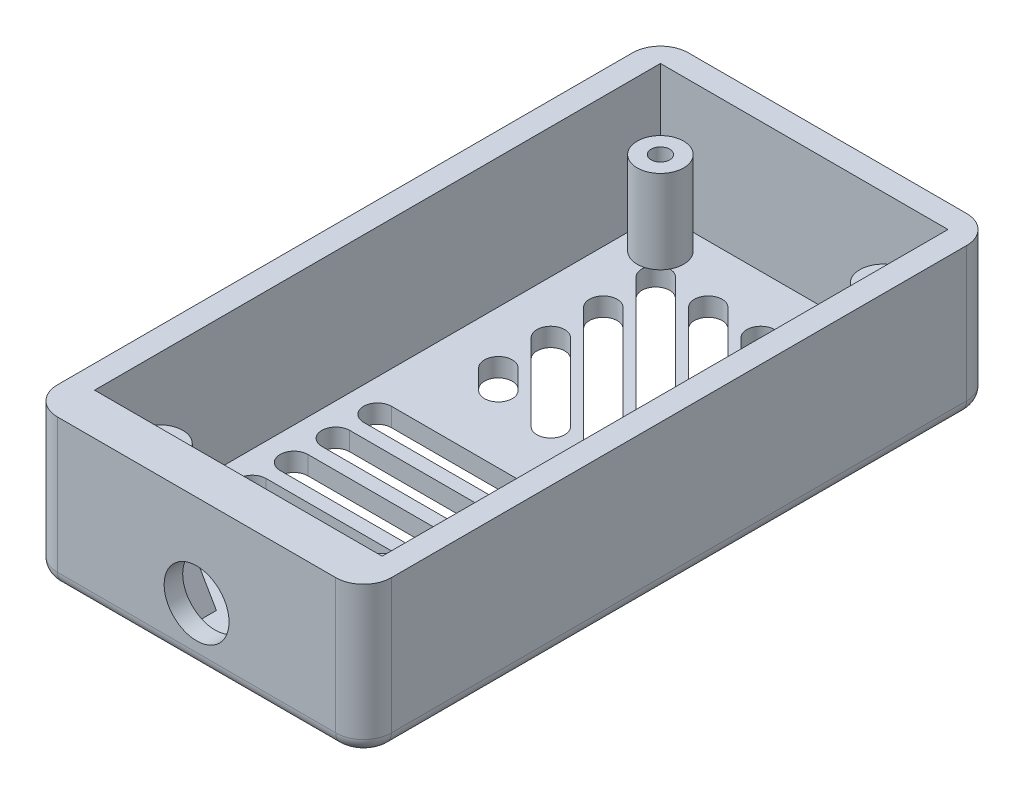
SolidWorks part; units mm, degrees
ref_plane "前视基准面" through (0, 0, 0) normal (0, 0, 1) x (1, 0, 0)
ref_plane "上视基准面" through (0, 0, 0) normal (0, 1, 0) x (1, 0, 0)
ref_plane "右视基准面" through (0, 0, 0) normal (1, 0, 0) x (0, 0, -1)
sketch "草图1" plane through (0, 0, 0) normal (0, 1, 0) x (1, 0, 0)
  line L0 (-15, 30) -> (15, -30) construction
  line L1 (18, -33) -> (-18, -33)
  line L2 (18, -33) -> (18, 33)
  line L3 (18, 33) -> (-18, 33)
  line L4 (-18, -33) -> (-18, 33)
  line L5 (18, -33) -> (-18, 33) construction
  line L6 (18, 33) -> (-18, -33) construction
  line L11 (15.9587, -29.2575) -> (-14.6614, 26.8792) construction
  line L12 (15, 28.2353) -> (-15, -28.2353) construction
  line L13 (-15, 30) -> (15, 30)
  line L14 (-15, 30) -> (-15, -30)
  line L15 (-15, -30) -> (15, -30)
  line L16 (15, 30) -> (15, -30)
  line L17 (0, -30) -> (0, 30) construction
  line L18 (15, 0) -> (-15, 0) construction
  circle A0 centre (-12, 27) radius 1.05
  circle A1 centre (12, 27) radius 1.05
  circle A2 centre (12, -27) radius 1.05
  circle A3 centre (-12, -27) radius 1.05
  point P0 (0, 0)
  point P6 (0, 0)
  point P15 (0, 0)
  dimension "D6" = 3
  dimension "D7" = 2.1
  dimension "D1" = 36
  dimension "D2" = 66
  dimension "D3" = 60
  dimension "D4" = 30
  dimension "D5" = 3
extrude "凸台-拉伸1" add sketch "草图1" along normal blind 16 contours L4 L1 L2 L3 L13 L16 L15 L14 | L16 L13 L14 L15 A1 A0 A2 A3 | A3 | A2 | A0 | A1
sketch "草图2" plane through (0, 16, 0) normal (0, 1, 0) x (1, 0, 0)
  line L0 (15.5, -30.5) -> (-15.5, 30.5) construction
  line L1 (-15.5, 30.5) -> (15.5, 30.5)
  line L2 (-15.5, 30.5) -> (-15.5, -30.5)
  line L3 (-15.5, -30.5) -> (15.5, -30.5)
  line L4 (15.5, 30.5) -> (15.5, -30.5)
  point P6 (0, 0)
  dimension "D1" = 31
  dimension "D2" = 61
extrude "切除-拉伸1" cut sketch "草图2" against normal blind 14
sketch "草图3" plane through (0, 2, 0) normal (0, 1, 0) x (1, 0, 0)
  circle A0 centre (-12, 27) radius 2.5
  circle A1 centre (12, 27) radius 2.5
  circle A2 centre (12, -27) radius 2.5
  circle A3 centre (-12, -27) radius 2.5
  circle A4 centre (-12, 27) radius 1
  circle A5 centre (12, 27) radius 1
  circle A6 centre (12, -27) radius 1
  circle A7 centre (-12, -27) radius 1
  dimension "D1" = 5
extrude "凸台-拉伸4" add sketch "草图3" along normal blind 9 separate body
sketch "草图6" plane through (0, 0, 33) normal (0, 0, 1) x (1, 0, 0)
  line L1 (-18, 0) -> (18, 0)
  line L2 (-18, 0) -> (-18, 16)
  line L3 (-18, 16) -> (18, 16)
  line L4 (18, 0) -> (18, 16)
extrude "凸台-拉伸5" add sketch "草图6" along normal blind 2
sketch "草图7" plane through (0, 0, 30.5) normal (0, 0, -1) x (-1, 0, 0)
  line L0 (-18, 0) -> (18, 0) construction
  line L1 (2.3671, 10.2) -> (-2.3671, 10.2)
  line L2 (-2.3671, 10.2) -> (-4.7343, 6.1)
  line L3 (-4.7343, 6.1) -> (-2.3671, 2)
  line L4 (-2.3671, 2) -> (2.3671, 2)
  line L5 (2.3671, 2) -> (4.7343, 6.1)
  line L6 (4.7343, 6.1) -> (2.3671, 10.2)
  line L7 (0, 6.1) -> (0, 0) construction
  circle A0 centre (0, 6.1) radius 4.1 construction
  dimension "D1" = 2
  dimension "D2" = 8.2
extrude "切除-拉伸2" cut sketch "草图7" against normal blind 2.5
sketch "草图9" plane through (0, 0, 33) normal (0, 0, -1) x (-1, 0, 0)
  line L0 (4.7343, 6.1) -> (-4.7343, 6.1) construction
  line L1 (2.3671, 2) -> (4.7343, 6.1) construction
  line L2 (-4.7343, 6.1) -> (-2.3671, 2) construction
  circle A0 centre (0, 6.1) radius 3.5
  dimension "D1" = 7
extrude "切除-拉伸3" cut sketch "草图9" against normal through all
fillet "圆角1" radius 3 4 edges at (-18, 8, 35) (18, 8, 35) (18, 8, -33) (-18, 8, -33)
fillet "圆角2" radius 1.5 8 edges at (17.1213, 0, 34.1213) (18, 0, 1) (17.1213, 0, -32.1213) (0, 0, -33) (-17.1213, 0, -32.1213) (-18, 0, 1) (-17.1213, 0, 34.1213) (0, 0, 35)
sketch "草图13" plane through (0, 0, 0) normal (0, -1, 0) x (1, 0, 0)
  line L24 (-12, 17) -> (12, 17) construction
  line L25 (0, 0) -> (0, -14.5) construction
  line L26 (-12, 18.5) -> (12, 18.5)
  line L39 (-12, 15.5) -> (12, 15.5)
  line L41 (-15.5, 30.5) -> (15.5, 30.5) construction
  line L42 (0, 17) -> (0, 0) construction
  line L43 (-12, 12.5) -> (12, 12.5) construction
  line L44 (-12, 14) -> (12, 14)
  line L45 (-12, 11) -> (12, 11)
  line L46 (-12, 8) -> (12, 8) construction
  line L47 (-12, 9.5) -> (12, 9.5)
  line L48 (-12, 6.5) -> (12, 6.5)
  line L49 (-12, 3.5) -> (12, 3.5) construction
  line L50 (-12, 5) -> (12, 5)
  line L51 (-12, 2) -> (12, 2)
  line L52 (-10, -4.5) -> (10, -24.5) construction
  line L53 (15, -33) -> (-15, -33) construction
  line L54 (15.5, -30.5) -> (-15.5, -30.5) construction
  line L55 (-9.8169, -7.3464) -> (-7.6956, -5.2251) construction
  line L56 (-10.8776, -6.2857) -> (-8.7563, -4.1644)
  line L57 (-8.7563, -8.407) -> (-6.635, -6.2857)
  line L58 (-9.8169, -13.0032) -> (-1.4968, -4.6831) construction
  line L59 (-10.8776, -11.9426) -> (-2.5574, -3.6224)
  line L60 (-8.7563, -14.0639) -> (-0.4361, -5.7437)
  line L61 (-9.8169, -18.6601) -> (4.1601, -4.6831) construction
  line L62 (-10.8776, -17.5994) -> (3.0994, -3.6224)
  line L63 (-8.7563, -19.7208) -> (5.2208, -5.7437)
  line L64 (-9.8169, -24.3169) -> (9.8169, -4.6831) construction
  line L65 (-10.8776, -23.2563) -> (8.7563, -3.6224)
  line L66 (-8.7563, -25.3776) -> (10.8776, -5.7437)
  line L67 (-9.8169, -24.3169) -> (15.4978, 0.9978) construction
  line L70 (7.1536, -24.3169) -> (9.2749, -22.1956) construction
  line L73 (8.2143, -25.3776) -> (10.3356, -23.2563)
  line L76 (6.093, -23.2563) -> (8.2143, -21.135)
  line L79 (-9.8169, -7.3464) -> (-9.8169, -26.6109) construction
  line L82 (1.4968, -24.3169) -> (9.8169, -15.9968) construction
  line L83 (2.5574, -25.3776) -> (10.8776, -17.0574)
  line L84 (0.4361, -23.2563) -> (8.7563, -14.9361)
  line L85 (-4.1601, -24.3169) -> (9.8169, -10.3399) construction
  line L86 (-3.0994, -25.3776) -> (10.8776, -11.4006)
  line L87 (-5.2208, -23.2563) -> (8.7563, -9.2792)
  arc A0 (-12, 18.5) -> (-12, 15.5) centre (-12, 17) ccw
  arc A1 (12, 15.5) -> (12, 18.5) centre (12, 17) ccw
  arc A2 (-12, 14) -> (-12, 11) centre (-12, 12.5) ccw
  arc A3 (12, 11) -> (12, 14) centre (12, 12.5) ccw
  arc A4 (-12, 9.5) -> (-12, 6.5) centre (-12, 8) ccw
  arc A5 (12, 6.5) -> (12, 9.5) centre (12, 8) ccw
  arc A6 (-12, 5) -> (-12, 2) centre (-12, 3.5) ccw
  arc A7 (12, 2) -> (12, 5) centre (12, 3.5) ccw
  arc A8 (-10.8776, -6.2857) -> (-8.7563, -8.407) centre (-9.8169, -7.3464) ccw
  arc A9 (-6.635, -6.2857) -> (-8.7563, -4.1644) centre (-7.6956, -5.2251) ccw
  arc A10 (-10.8776, -11.9426) -> (-8.7563, -14.0639) centre (-9.8169, -13.0032) ccw
  arc A11 (-0.4361, -5.7437) -> (-2.5574, -3.6224) centre (-1.4968, -4.6831) ccw
  arc A12 (-10.8776, -17.5994) -> (-8.7563, -19.7208) centre (-9.8169, -18.6601) ccw
  arc A13 (5.2208, -5.7437) -> (3.0994, -3.6224) centre (4.1601, -4.6831) ccw
  arc A14 (-10.8776, -23.2563) -> (-8.7563, -25.3776) centre (-9.8169, -24.3169) ccw
  arc A15 (10.8776, -5.7437) -> (8.7563, -3.6224) centre (9.8169, -4.6831) ccw
  arc A24 (8.2143, -25.3776) -> (6.093, -23.2563) centre (7.1536, -24.3169) cw
  arc A25 (8.2143, -21.135) -> (10.3356, -23.2563) centre (9.2749, -22.1956) cw
  arc A26 (2.5574, -25.3776) -> (0.4361, -23.2563) centre (1.4968, -24.3169) cw
  arc A27 (8.7563, -14.9361) -> (10.8776, -17.0574) centre (9.8169, -15.9968) cw
  arc A28 (-3.0994, -25.3776) -> (-5.2208, -23.2563) centre (-4.1601, -24.3169) cw
  arc A29 (8.7563, -9.2792) -> (10.8776, -11.4006) centre (9.8169, -10.3399) cw
  point P2 (0, 17)
  point P15 (0, 12.5)
  point P22 (0, 8)
  point P29 (0, 3.5)
  point P38 (0, -14.5)
  point P41 (-8.7563, -6.2857)
  point P48 (-5.6569, -8.8431)
  point P53 (-2.8284, -11.6716)
  point P60 (0, -14.5)
  point P72 (8.2143, -23.2563)
  point P79 (5.6569, -20.1569)
  point P86 (2.8284, -17.3284)
  dimension "D3" = 1.5
  dimension "D9" = 1.5
  dimension "D1" = 12
  dimension "D2" = 24
  dimension "D5" = 45
  dimension "D6" = 20
  dimension "D7" = 6
  dimension "D8" = 3
  dimension "D10" = 90
  dimension "D11" = 1
  dimension "D12" = 1
  dimension "D13" = 1
  dimension "D4" = 4
extrude "切除-拉伸4" cut sketch "草图13" against normal blind 2
